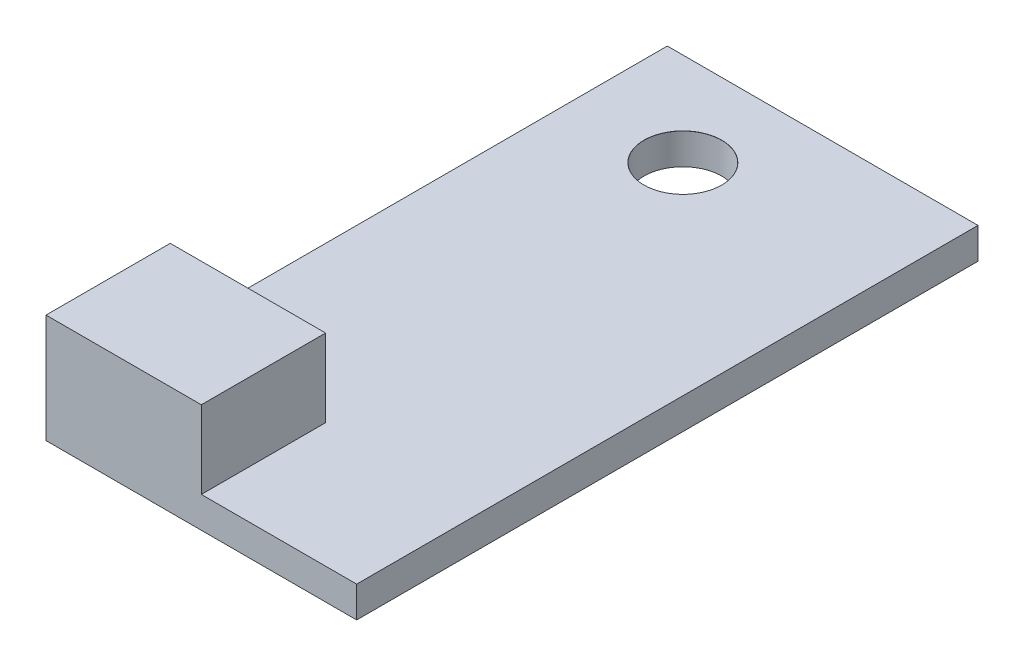
SolidWorks part; units mm, degrees
ref_plane "Front Plane" through (0, 0, 0) normal (0, 0, 1) x (1, 0, 0)
ref_plane "Top Plane" through (0, 0, 0) normal (0, 1, 0) x (1, 0, 0)
ref_plane "Right Plane" through (0, 0, 0) normal (1, 0, 0) x (0, 0, -1)
sketch "Sketch1" plane through (0, 0, 0) normal (0, 1, 0) x (1, 0, 0)
  line L1 (0, 0) -> (100, 0)
  line L2 (0, 0) -> (0, 200)
  line L3 (0, 200) -> (100, 200)
  line L4 (100, 0) -> (100, 200)
  dimension "D1" = 100
  dimension "D2" = 200
extrude "Boss-Extrude1" add sketch "Sketch1" along normal blind 10
sketch "Sketch3" plane through (0, 10, 0) normal (0, 1, 0) x (1, 0, 0)
  line L1 (0, 0) -> (50, 0)
  line L2 (0, 0) -> (0, 40)
  line L3 (0, 40) -> (50, 40)
  line L4 (50, 0) -> (50, 40)
  dimension "D1" = 50
  dimension "D2" = 40
extrude "Boss-Extrude2" add sketch "Sketch3" along normal blind 25
hole_wizard "Ø25.0 (25) Diameter Hole2" positions "Sketch8" profile "Sketch9" hole size "Ø25.0" standard "ANSI Metric" end condition through all
sketch "Sketch8" plane through (0, 10, 0) normal (0, 1, 0) x (1, 0, 0)
  line L0 (0, 200) -> (0, 40) construction
  line L1 (100, 200) -> (0, 200) construction
  point P0 (35, 170)
  point P9 (26.5558, 159.4975)
  point P12 (0, 0)
  point P13 (0, 0)
  dimension "D1" = 35
  dimension "D2" = 30
sketch "Sketch9" plane through (35, 10, -170) normal (1, 0, 0) x (0, 0, 1)
  line L0 (0, 0) -> (0, 10)
  line L1 (0, 10) -> (12.5, 10)
  line L2 (12.5, 10) -> (12.5, 0.025)
  line L3 (12.5, 0.025) -> (12.525, 0)
  line L5 (12.525, 0) -> (0, 0)
  line L6 (-12.5, 0.025) -> (-12.525, 0) construction
  line L11 (0, -6.35) -> (0, 107.95) construction
  dimension "Thru Hole Dia." = 25
  dimension "Thru Hole Depth" = 10
  dimension "Near C'Sink Dia." = 25.05
  dimension "Near C'Sink Angle" = 90
